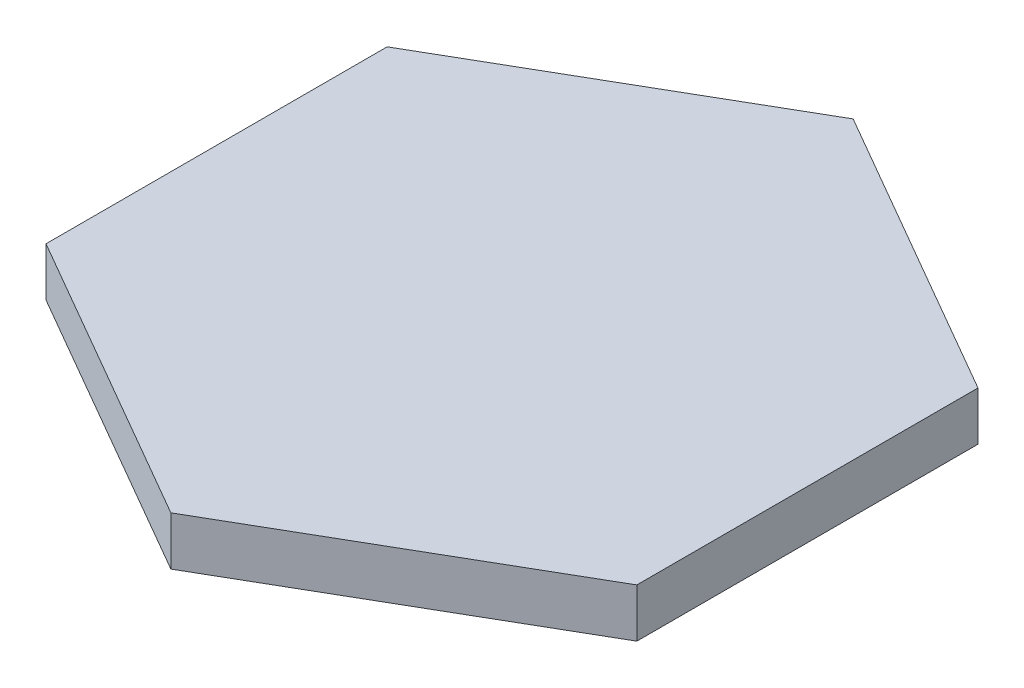
SolidWorks part; units mm, degrees
ref_plane "Front Plane" through (0, 0, 0) normal (0, 0, 1) x (1, 0, 0)
ref_plane "Top Plane" through (0, 0, 0) normal (0, 1, 0) x (1, 0, 0)
ref_plane "Right Plane" through (0, 0, 0) normal (1, 0, 0) x (0, 0, -1)
sketch "Sketch1" plane through (0, 0, 0) normal (0, 1, 0) x (1, 0, 0)
  line L1 (0, 88.9) -> (-76.9897, 44.45)
  line L2 (-76.9897, 44.45) -> (-76.9897, -44.45)
  line L3 (-76.9897, -44.45) -> (0, -88.9)
  line L4 (0, -88.9) -> (76.9897, -44.45)
  line L5 (76.9897, -44.45) -> (76.9897, 44.45)
  line L6 (76.9897, 44.45) -> (0, 88.9)
  circle A0 centre (0, 0) radius 76.9897 construction
  dimension "D1" = 177.8
extrude "Boss-Extrude1" add sketch "Sketch1" along normal blind 12.7
